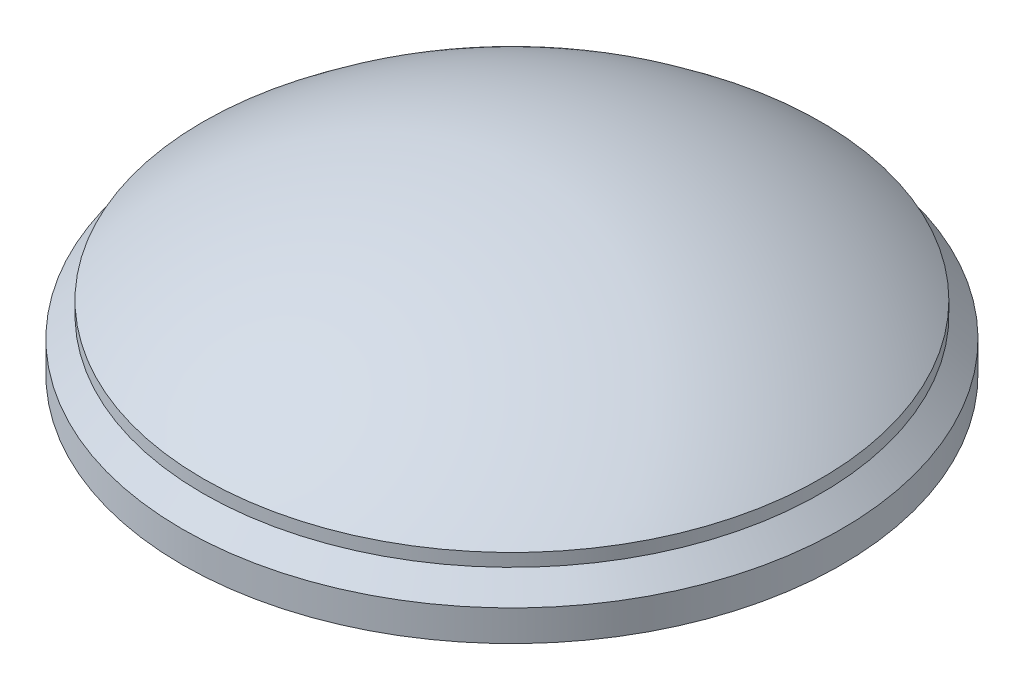
SolidWorks part; units mm, degrees
ref_plane "Front Plane" through (0, 0, 0) normal (0, 0, 1) x (1, 0, 0)
ref_plane "Top Plane" through (0, 0, 0) normal (0, 1, 0) x (1, 0, 0)
ref_plane "Right Plane" through (0, 0, 0) normal (1, 0, 0) x (0, 0, -1)
sketch "Sketch1" plane through (0, 0, 0) normal (0, 0, 1) x (1, 0, 0)
  line L0 (0, 289.4176) -> (0, -245.5209) construction
  line L1 (-64, 16) -> (-56, 16)
  line L2 (-64, 16) -> (-64, 22)
  line L3 (-64, 22) -> (-60, 26)
  line L4 (-60, 26) -> (-60, 28.5)
  line L5 (0, 49.8454) -> (0, 39.8454)
  line L6 (-56, 18.7907) -> (-56, 16)
  arc A1 (-60, 28.5) -> (0, 49.8454) centre (0, -45.1546) cw
  arc A2 (0, 39.8454) -> (-56, 18.7907) centre (0, -45.1546) ccw
  dimension "D1" = 16
  dimension "D2" = 10
  dimension "D6" = 95
  dimension "D8" = 135
  dimension "D3" = 6
  dimension "D4" = 2.5
  dimension "D5" = 4
  dimension "D7" = 8
revolve "Revolve1" add sketch "Sketch1" angle 360 about L0
